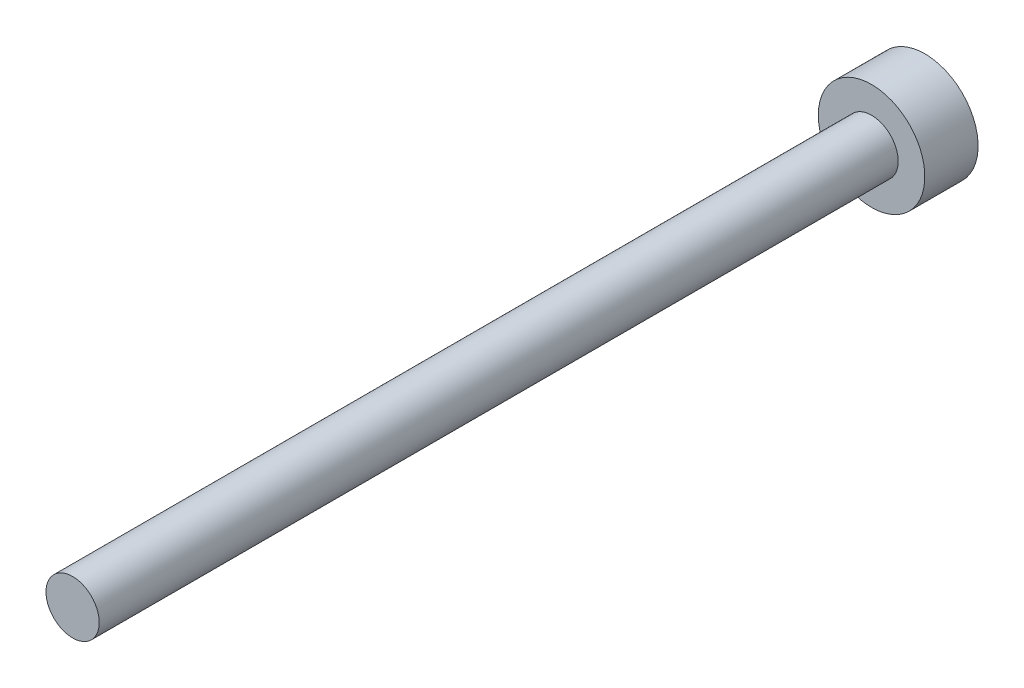
SolidWorks part; units mm, degrees
ref_plane "前视基准面" through (0, 0, 0) normal (0, 0, 1) x (1, 0, 0)
ref_plane "上视基准面" through (0, 0, 0) normal (0, 1, 0) x (1, 0, 0)
ref_plane "右视基准面" through (0, 0, 0) normal (1, 0, 0) x (0, 0, -1)
sketch "草图1" plane through (0, 0, 0) normal (0, 0, 1) x (1, 0, 0)
  circle A0 centre (0, 0) radius 1.5
  dimension "D1" = 3
extrude "凸台-拉伸1" add sketch "草图1" along normal blind 45
cosmetic thread "装饰螺纹线1" parameters "D1"=5, "D2"=2
sketch "草图2" plane through (0, 0, 0) normal (0, 0, -1) x (-1, 0, 0)
  circle A0 centre (0, 0) radius 3
  dimension "D1" = 6
extrude "凸台-拉伸2" add sketch "草图2" along normal blind 3
